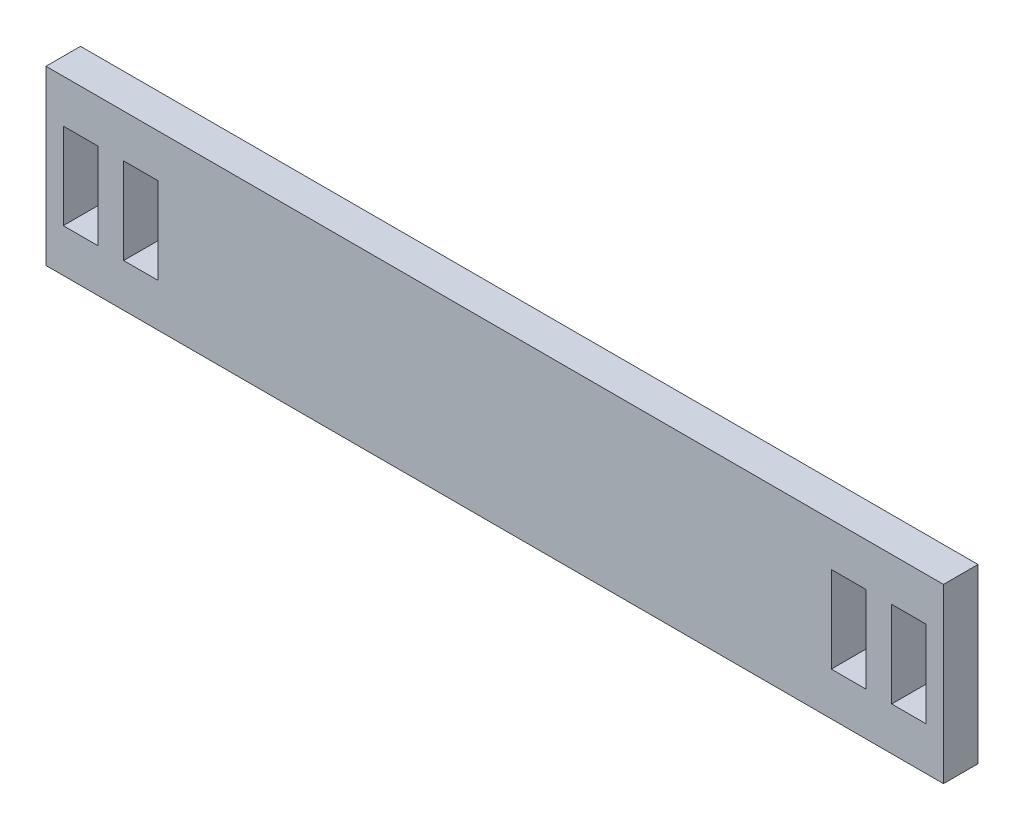
SolidWorks part; units mm, degrees
ref_plane "前视基准面" through (0, 0, 0) normal (0, 0, 1) x (1, 0, 0)
ref_plane "上视基准面" through (0, 0, 0) normal (0, 1, 0) x (1, 0, 0)
ref_plane "右视基准面" through (0, 0, 0) normal (1, 0, 0) x (0, 0, -1)
sketch "草图1" plane through (0, 0, 0) normal (0, 0, 1) x (1, 0, 0)
  line L2 (0, -55) -> (0, 55) construction
  line L3 (-46, 0) -> (46, 0)
  line L4 (-52, 0) -> (-52, 20)
  line L5 (-46, 20) -> (46, 20)
  line L6 (52, 0) -> (52, 20)
  line L7 (46, 15) -> (50, 15)
  line L8 (46, 15) -> (46, 5)
  line L9 (46, 5) -> (50, 5)
  line L10 (50, 15) -> (50, 5)
  line L11 (-46, 5) -> (-50, 5)
  line L12 (-50, 15) -> (-50, 5)
  line L13 (-46, 15) -> (-50, 15)
  line L14 (-46, 15) -> (-46, 5)
  line L29 (-46, 20) -> (-52, 20)
  line L30 (-46, 0) -> (-52, 0)
  line L31 (52, 20) -> (46, 20)
  line L32 (52, 0) -> (46, 0)
  line L33 (43, 5) -> (39, 5)
  line L34 (-43, 15) -> (-39, 15)
  line L35 (-43, 15) -> (-43, 5)
  line L36 (-43, 5) -> (-39, 5)
  line L37 (-39, 15) -> (-39, 5)
  line L38 (39, 15) -> (39, 5)
  line L39 (43, 15) -> (39, 15)
  line L40 (43, 15) -> (43, 5)
extrude "凸台-拉伸1" add sketch "草图1" along normal mid plane 4
